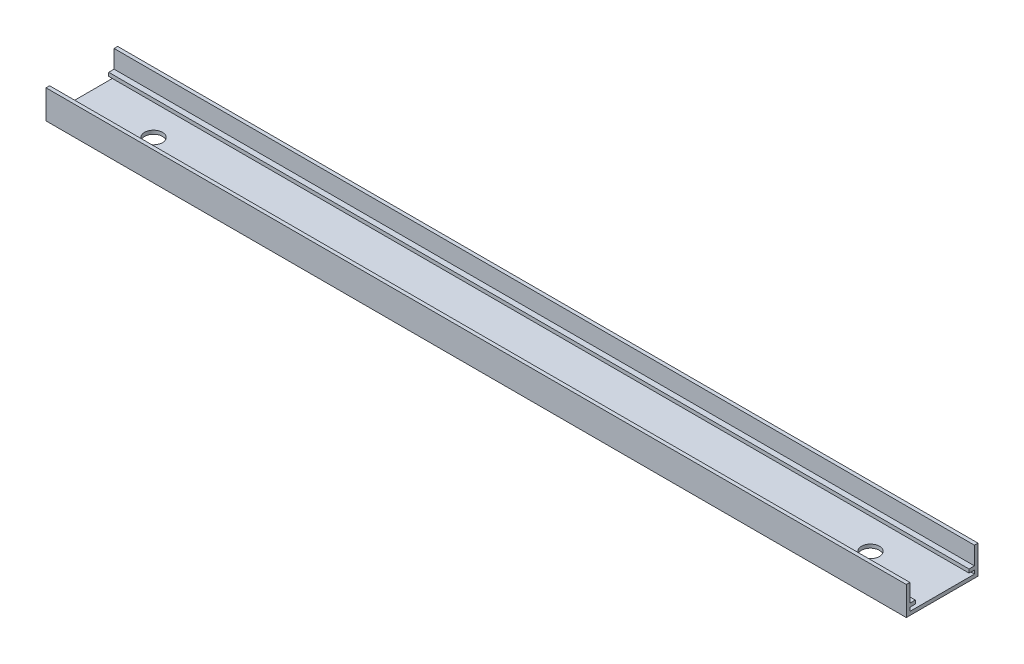
SolidWorks part; units mm, degrees
ref_plane "Front Plane" through (0, 0, 0) normal (0, 0, 1) x (1, 0, 0)
ref_plane "Top Plane" through (0, 0, 0) normal (0, 1, 0) x (1, 0, 0)
ref_plane "Right Plane" through (0, 0, 0) normal (1, 0, 0) x (0, 0, -1)
sketch "Sketch1" plane through (0, 0, 0) normal (1, 0, 0) x (0, 0, -1)
  line L0 (0, 0) -> (25.4, 0)
  line L1 (0, 0) -> (0, 10.16)
  line L2 (0, 10.16) -> (1.27, 10.16)
  line L3 (1.27, 10.16) -> (1.27, 3.81)
  line L4 (1.27, 3.81) -> (3.1759, 3.81)
  line L5 (3.1759, 3.81) -> (3.1759, 2.54)
  line L6 (3.1759, 2.54) -> (1.27, 2.54)
  line L7 (1.27, 2.54) -> (1.27, 1.27)
  line L8 (1.27, 1.27) -> (24.13, 1.27)
  line L10 (24.13, 2.54) -> (24.13, 1.27)
  line L11 (22.2241, 2.54) -> (24.13, 2.54)
  line L12 (22.2241, 3.81) -> (22.2241, 2.54)
  line L13 (24.13, 3.81) -> (22.2241, 3.81)
  line L14 (24.13, 10.16) -> (24.13, 3.81)
  line L15 (25.4, 10.16) -> (24.13, 10.16)
  line L16 (25.4, 0) -> (25.4, 10.16)
  dimension "D1" = 25.4
  dimension "D2" = 10.16
  dimension "D3" = 1.27
  dimension "D4" = 1.27
  dimension "D5" = 1.27
  dimension "D6" = 1.27
  dimension "D7" = 6.35
extrude "Boss-Extrude1" add sketch "Sketch1" against normal blind 304.8
sketch "Sketch2" plane through (0, 1.27, 0) normal (0, 1, 0) x (1, 0, 0)
  line L0 (-304.8, 12.7) -> (0, 12.7) construction
  line L1 (-304.8, 24.13) -> (-304.8, 1.27) construction
  line L2 (0, 24.13) -> (0, 1.27) construction
  line L3 (-152.4, 22.2241) -> (-152.4, 3.1759) construction
  line L4 (-304.8, 22.2241) -> (0, 22.2241) construction
  line L5 (-304.8, 3.1759) -> (0, 3.1759) construction
  circle A0 centre (-279.4, 12.7) radius 3.175
  circle A1 centre (-25.4, 12.7) radius 3.175
  dimension "D1" = 6.35
  dimension "D2" = 25.4
extrude "Cut-Extrude2" cut sketch "Sketch2" against normal through all
